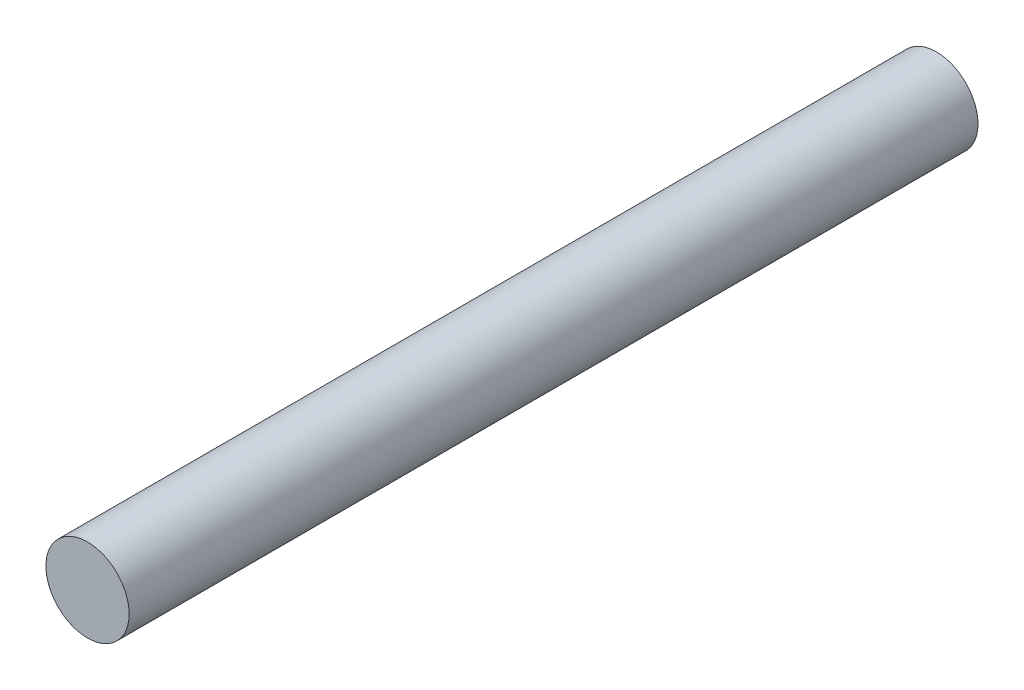
SolidWorks part; units mm, degrees
ref_plane "Front Plane" through (0, 0, 0) normal (0, 0, 1) x (1, 0, 0)
ref_plane "Top Plane" through (0, 0, 0) normal (0, 1, 0) x (1, 0, 0)
ref_plane "Right Plane" through (0, 0, 0) normal (1, 0, 0) x (0, 0, -1)
sketch "Sketch1" plane through (0, 0, 0) normal (0, 0, 1) x (1, 0, 0)
  circle A0 centre (0, 0) radius 10
extrude "Boss-Extrude1" add sketch "Sketch1" along normal blind 204
